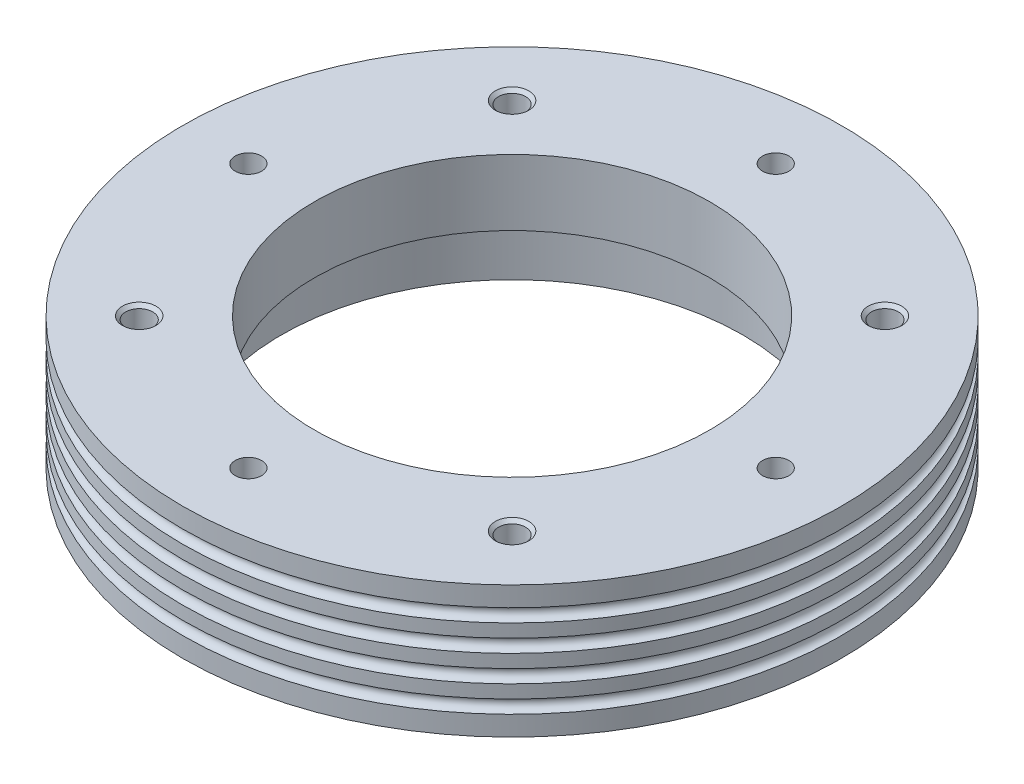
SolidWorks part; units mm, degrees
ref_plane "前视基准面" through (0, 0, 0) normal (0, 0, 1) x (1, 0, 0)
ref_plane "上视基准面" through (0, 0, 0) normal (0, 1, 0) x (1, 0, 0)
ref_plane "右视基准面" through (0, 0, 0) normal (1, 0, 0) x (0, 0, -1)
sketch "草图1" plane through (0, 0, 0) normal (0, 1, 0) x (1, 0, 0)
  circle A0 centre (0, 0) radius 25
  dimension "D1" = 50
extrude "凸台-拉伸1" add sketch "草图1" along normal blind 10
sketch "草图2" plane through (0, 10, 0) normal (0, 1, 0) x (1, 0, 0)
  circle A0 centre (0, 0) radius 20 construction
  point P3 (20, 0)
  point P4 (0, 20)
  point P5 (-20, 0)
  point P6 (0, -20)
  dimension "D1" = 40
hole_wizard "孔1" positions "草图2" profile "草图3" legacy end condition up to next
sketch "草图3" plane through (0, 10, 20) normal (1, 0, 0) x (0, 0, 1)
  line L0 (0, 0) -> (0, 10)
  line L1 (0, 10) -> (1, 10)
  line L2 (1, 10) -> (1, 0)
  line L3 (1, 0) -> (0, 0)
  line L4 (0, 110) -> (0, -10) construction
  dimension "直径" = 2
  dimension "深度" = 10
sketch "草图4" plane through (0, 0, 0) normal (0, -1, 0) x (1, 0, 0)
  circle A0 centre (0, 0) radius 17.5
  dimension "D1" = 35
extrude "切除-拉伸1" cut sketch "草图4" against normal blind 5
sketch "草图5" plane through (0, 5, 0) normal (0, -1, 0) x (1, 0, 0)
  circle A0 centre (0, 0) radius 15
  dimension "D1" = 30
extrude "切除-拉伸2" cut sketch "草图5" against normal blind 5
sketch "草图6" plane through (0, 10, 0) normal (0, 1, 0) x (1, 0, 0)
  line L0 (0, 0) -> (14.1421, 14.1421) construction
  line L2 (-5.5, 0) -> (5.5, 0) construction
  circle A0 centre (0, 0) radius 20 construction
  point P9 (14.1421, 14.1421)
  point P27 (14.1421, -14.1421)
  point P28 (-14.1421, -14.1421)
  point P29 (-14.1421, 14.1421)
  dimension "D1" = 40
  dimension "D2" = 45
  dimension "D3" = 4
hole_wizard "M2.5 螺纹孔1" positions "草图6" profile "草图8" tap size "M2.5" standard "GB" end condition up to next
sketch "草图8" plane through (-14.1421, 10, -14.1421) normal (1, 0, 0) x (0, 0, 1)
  line L0 (0, 0) -> (0, 10)
  line L1 (0, 10) -> (1.025, 10)
  line L2 (1.025, 10) -> (1.025, 0.25)
  line L3 (1.025, 0.25) -> (1.275, 0)
  line L5 (1.275, 0) -> (0, 0)
  line L6 (-1.025, 0.25) -> (-1.275, 0) construction
  line L11 (0, -6.35) -> (0, 107.95) construction
  dimension "通孔螺纹孔钻头直径" = 2.05
  dimension "通孔螺纹孔钻头深度" = 10
  dimension "近端锥形沉头孔直径" = 2.55
  dimension "近端锥形沉头孔角度" = 90
cosmetic thread "孔螺纹线1" parameters "D2"=2.5
cosmetic thread "孔螺纹线2" parameters "D2"=2.5
cosmetic thread "孔螺纹线3" parameters "D2"=2.5
cosmetic thread "孔螺纹线4" parameters "D2"=2.5
ref_plane "基准面1" through (0, 2, 0) normal (0, 1, 0) x (1, 0, 0)
sketch "草图11" plane through (0, 2, 0) normal (0, 1, 0) x (1, 0, 0)
  circle A0 centre (0, 0) radius 25
  dimension "D1" = 50
sweep "切除-扫描1" cut path "草图11" circular profile diameter 1 parameters "D3"=1
pattern_linear "阵列(线性)1" count 4 spacing 2 along (0, 1, 0) of "切除-扫描1"
